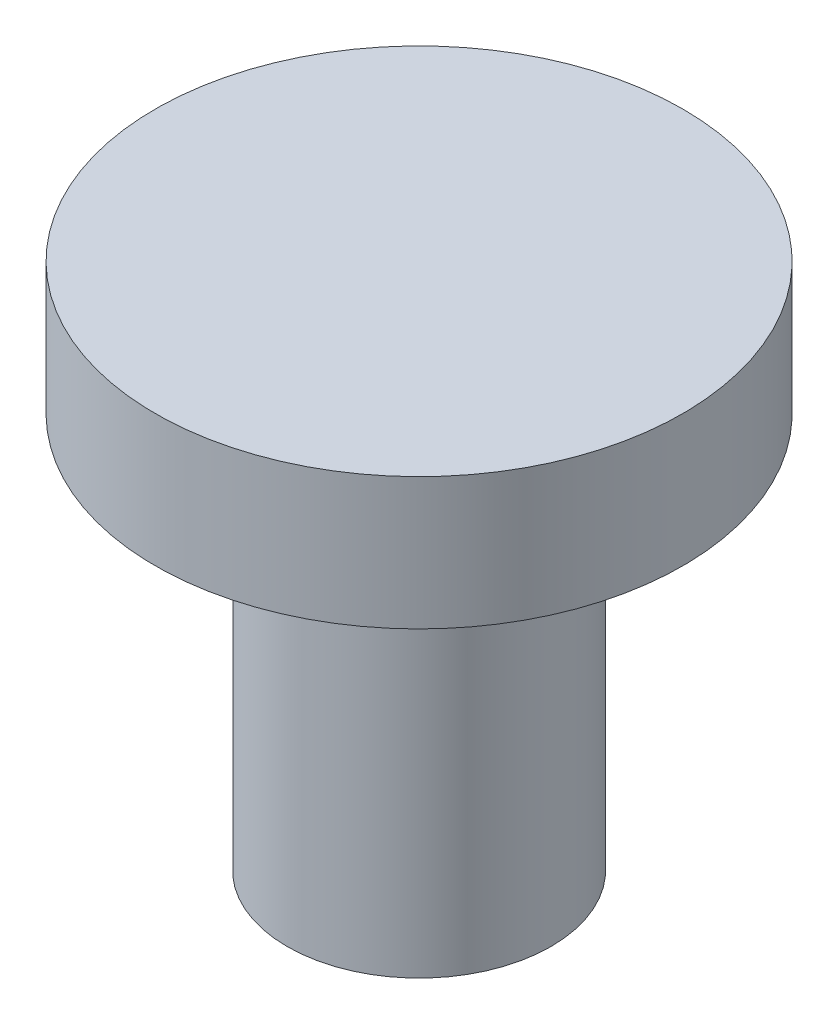
SolidWorks part; units mm, degrees
ref_plane "Front Plane" through (0, 0, 0) normal (0, 0, 1) x (1, 0, 0)
ref_plane "Top Plane" through (0, 0, 0) normal (0, 1, 0) x (1, 0, 0)
ref_plane "Right Plane" through (0, 0, 0) normal (1, 0, 0) x (0, 0, -1)
sketch "Sketch1" plane through (0, 0, 0) normal (0, 0, 1) x (1, 0, 0)
  line L0 (2, 4) -> (0, 4)
  line L1 (0, 4) -> (0, 0)
  line L2 (0, 0) -> (1, 0)
  line L3 (1, 0) -> (1, 3)
  line L4 (1, 3) -> (2, 3)
  line L5 (2, 3) -> (2, 4)
  line L6 (0, 4) -> (0, 0) construction
  point P6 (-4.0809, 3.5184)
  point P7 (-4.0737, 4.0514)
  point P8 (0, 0)
  point P9 (0, 0)
  point P10 (0, 0)
  dimension "D1" = 1
  dimension "D2" = 2
  dimension "D3" = 3
  dimension "D4" = 4
revolve "Revolve1" add sketch "Sketch1" angle 360 about L6
